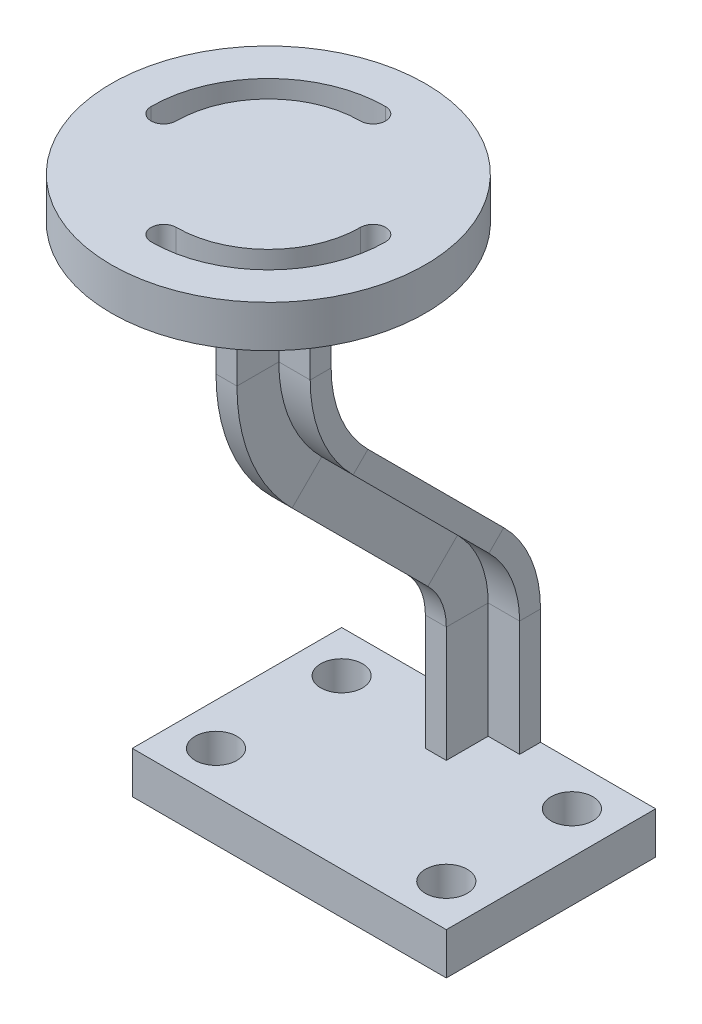
SolidWorks part; units mm, degrees
ref_plane "Front Plane" through (0, 0, 0) normal (0, 0, 1) x (1, 0, 0)
ref_plane "Top Plane" through (0, 0, 0) normal (0, 1, 0) x (1, 0, 0)
ref_plane "Right Plane" through (0, 0, 0) normal (1, 0, 0) x (0, 0, -1)
sketch "Sketch1" plane through (0, 0, 0) normal (0, 1, 0) x (1, 0, 0)
  line L0 (43.2701, -37.6126) -> (43.2701, 22.3874) construction
  line L1 (-86.7299, 42.3874) -> (63.2701, 42.3874)
  line L2 (-86.7299, 42.3874) -> (-86.7299, -57.6126)
  line L3 (-86.7299, -57.6126) -> (63.2701, -57.6126)
  line L4 (63.2701, 42.3874) -> (63.2701, -57.6126)
  line L5 (43.2701, 22.3874) -> (-66.7299, 22.3874) construction
  line L6 (-66.7299, 22.3874) -> (-66.7299, -37.6126) construction
  line L7 (-66.7299, -37.6126) -> (43.2701, -37.6126) construction
  circle A0 centre (43.2701, -37.6126) radius 10
  circle A1 centre (43.2701, 22.3874) radius 10
  circle A2 centre (-66.7299, 22.3874) radius 10
  circle A3 centre (-66.7299, -37.6126) radius 10
  dimension "D3" = 20
  dimension "D4" = 20
  dimension "D5" = 20
  dimension "D6" = 20
  dimension "D7" = 20
  dimension "D9" = 20
  dimension "D1" = 150
  dimension "D2" = 100
  dimension "D8" = 20
  dimension "D10" = 20
extrude "Boss-Extrude1" add sketch "Sketch1" along normal blind 20
sketch "Sketch3" plane through (0, 20, 0) normal (0, 1, 0) x (1, 0, 0)
  line L0 (-11.7299, 42.3874) -> (-11.7299, -57.6126) construction
  line L1 (63.2701, 42.3874) -> (-86.7299, 42.3874) construction
  line L2 (-86.7299, -57.6126) -> (63.2701, -57.6126) construction
ref_plane "Plane2" through (-11.7299, 0, 0) normal (-1, 0, 0) x (0, 0, 1)
sketch "Sketch4" plane through (-11.7299, 0, 0) normal (-1, 0, 0) x (0, 0, 1)
  line L0 (-42.3874, 20) -> (-42.3874, 75.1472)
  line L1 (-24.8138, 117.5736) -> (40.039, 182.4264)
  line L2 (57.6126, 224.8528) -> (57.6126, 280)
  arc A0 (-42.3874, 75.1472) -> (-24.8138, 117.5736) centre (17.6126, 75.1472) cw
  arc A1 (40.039, 182.4264) -> (57.6126, 224.8528) centre (-2.3874, 224.8528) ccw
  point P7 (-42.3874, 100)
  point P10 (57.6126, 200)
  dimension "D5" = 60
  dimension "D1" = 80
  dimension "D2" = 100
  dimension "D3" = 135
  dimension "D4" = 80
sketch "Sketch5" plane through (0, 20, 0) normal (0, 1, 0) x (1, 0, 0)
  line L0 (-31.7299, 42.3874) -> (8.2701, 42.3874)
  line L2 (-31.7299, 42.3874) -> (-31.7299, 32.3874)
  line L3 (-31.7299, 32.3874) -> (-16.7299, 32.3874)
  line L4 (8.2701, 42.3874) -> (8.2701, 32.3874)
  line L5 (63.2701, 42.3874) -> (-86.7299, 42.3874) construction
  line L6 (-16.7299, 32.3874) -> (-16.7299, 12.3874)
  line L7 (-16.7299, 12.3874) -> (-6.7299, 12.3874)
  line L8 (-6.7299, 12.3874) -> (-6.7299, 32.3874)
  line L9 (-6.7299, 32.3874) -> (8.2701, 32.3874)
  point P0 (-11.7299, 42.3874)
  dimension "D1" = 10
  dimension "D2" = 40
  dimension "D3" = 15
  dimension "D4" = 15
  dimension "D5" = 30
sweep "Sweep1" add profiles "Sketch5" path "Sketch4"
sketch "Sketch6" plane through (0, 280, 0) normal (0, 1, 0) x (1, 0, 0)
  line L0 (-16.7299, -67.6126) -> (-6.7299, -67.6126) construction
  circle A0 centre (-11.7299, -67.6126) radius 75
  circle A1 centre (-11.7299, -67.6126) radius 50 construction
  arc A2 (-61.7299, -67.6126) -> (-11.7299, -17.6126) centre (-11.7299, -67.6126) cw construction
  arc A3 (-11.7299, -11.6126) -> (-67.7299, -67.6126) centre (-11.7299, -67.6126) ccw
  arc A4 (-11.7299, -23.6126) -> (-55.7299, -67.6126) centre (-11.7299, -67.6126) ccw
  arc A5 (-11.7299, -23.6126) -> (-11.7299, -11.6126) centre (-11.7299, -17.6126) ccw
  arc A6 (-67.7299, -67.6126) -> (-55.7299, -67.6126) centre (-61.7299, -67.6126) ccw
  arc A7 (-11.7299, -117.6126) -> (38.2701, -67.6126) centre (-11.7299, -67.6126) ccw construction
  arc A8 (-11.7299, -123.6126) -> (44.2701, -67.6126) centre (-11.7299, -67.6126) ccw
  arc A9 (-11.7299, -111.6126) -> (32.2701, -67.6126) centre (-11.7299, -67.6126) ccw
  arc A10 (-11.7299, -111.6126) -> (-11.7299, -123.6126) centre (-11.7299, -117.6126) ccw
  arc A11 (44.2701, -67.6126) -> (32.2701, -67.6126) centre (38.2701, -67.6126) ccw
  point P9 (-47.0852, -32.2572)
  point P17 (23.6255, -102.9679)
  dimension "D1" = 150
  dimension "D2" = 100
  dimension "D3" = 6
  dimension "D4" = 6
extrude "Boss-Extrude2" add sketch "Sketch6" along normal blind 20 contours A0
